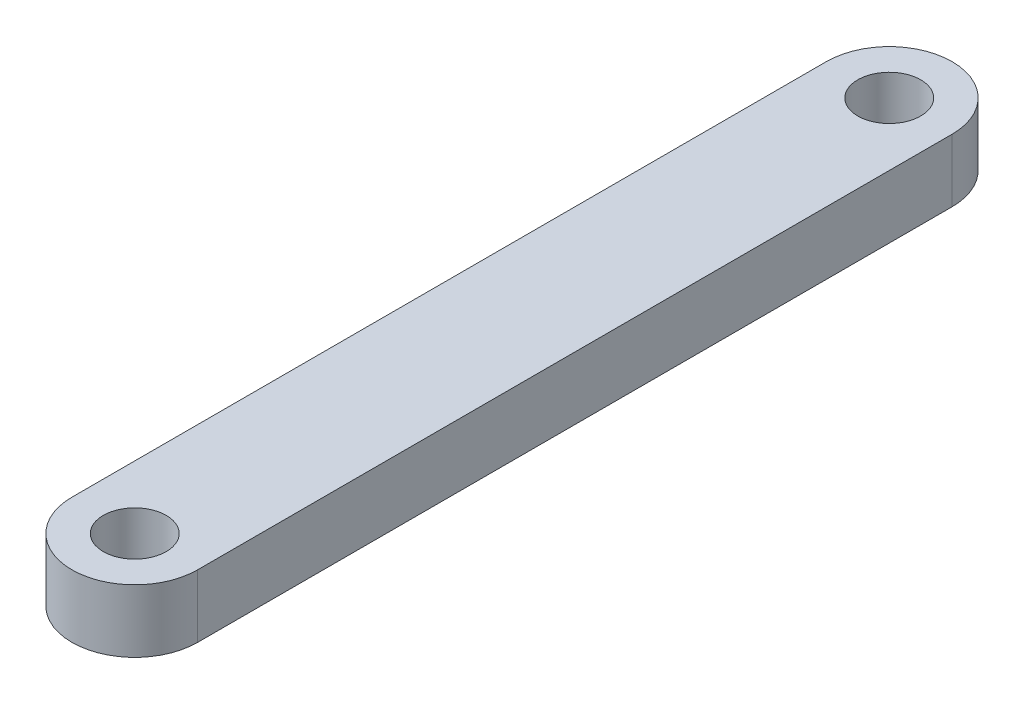
SolidWorks part; units mm, degrees
ref_plane "Plan de face" through (0, 0, 0) normal (0, 0, 1) x (1, 0, 0)
ref_plane "Plan de dessus" through (0, 0, 0) normal (0, 1, 0) x (1, 0, 0)
ref_plane "Plan de droite" through (0, 0, 0) normal (1, 0, 0) x (0, 0, -1)
sketch "Esquisse1" plane through (0, 0, 0) normal (0, 1, 0) x (1, 0, 0)
  line L0 (20.3844, -18) -> (-20.2781, -18) construction
  line L1 (-3, 0) -> (-3, -36)
  line L2 (3, 0) -> (3, -36)
  circle A0 centre (0, 0) radius 1.5
  arc A1 (3, 0) -> (-3, 0) centre (0, 0) ccw
  arc A2 (3, -36) -> (-3, -36) centre (0, -36) cw
  circle A3 centre (0, -36) radius 1.5
  point P10 (3, -18)
  point P11 (-3, -18)
  dimension "D1" = 3
  dimension "D2" = 3
  dimension "D3" = 18
extrude "Boss.-Extru.1" add sketch "Esquisse1" along normal blind 3
